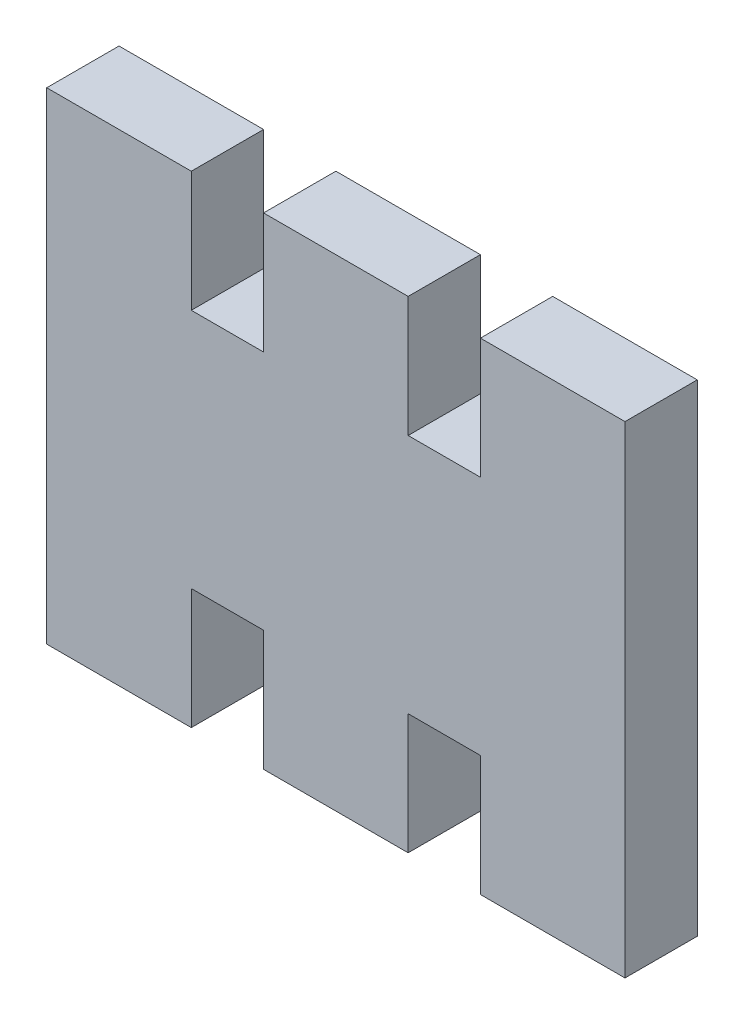
SolidWorks part; units mm, degrees
ref_plane "Front" through (0, 0, 0) normal (0, 0, 1) x (1, 0, 0)
ref_plane "Top" through (0, 0, 0) normal (0, 1, 0) x (1, 0, 0)
ref_plane "Right" through (0, 0, 0) normal (1, 0, 0) x (0, 0, -1)
sketch "Sketch1" plane through (0, 0, 0) normal (0, 0, 1) x (1, 0, 0)
  line L1 (0, 0) -> (-48, 0)
  line L2 (0, 0) -> (0, 40)
  line L3 (0, 40) -> (-48, 40)
  line L4 (-48, 0) -> (-48, 40)
  dimension "D1" = 48
  dimension "D2" = 40
extrude "Boss-Extrude1" add sketch "Sketch1" along normal blind 6
sketch "Sketch2" plane through (0, 0, 6) normal (0, 0, 1) x (1, 0, 0)
  line L0 (0, 40) -> (-48, 40) construction
  line L1 (-36, 40) -> (-30, 40)
  line L2 (-36, 40) -> (-36, 30)
  line L3 (-36, 30) -> (-30, 30)
  line L4 (-30, 40) -> (-30, 30)
  line L5 (-48, 40) -> (-48, 0) construction
  dimension "D1" = 6
  dimension "D2" = 12
  dimension "D3" = 10
extrude "Cut-Extrude1" cut sketch "Sketch2" against normal through all
pattern_linear "LPattern1" count 2 spacing 18 along (1, 0, 0) count 2 spacing 30 along (0, -1, 0) of "Cut-Extrude1"
